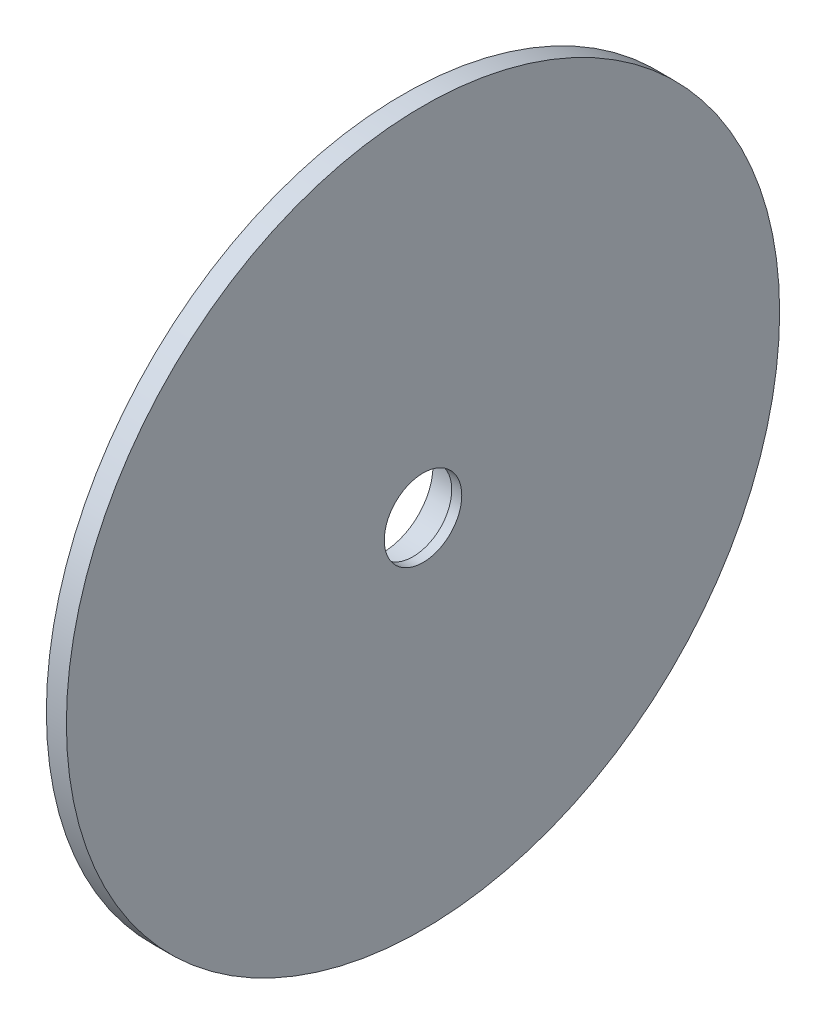
SolidWorks part; units mm, degrees
material "6061 Alloy"
ref_plane "Front Plane" through (0, 0, 0) normal (0, 0, 1) x (1, 0, 0)
ref_plane "Top Plane" through (0, 0, 0) normal (0, 1, 0) x (1, 0, 0)
ref_plane "Right Plane" through (0, 0, 0) normal (1, 0, 0) x (0, 0, -1)
sketch "Sketch1" plane through (0, 0, 0) normal (0, 0, 1) x (1, 0, 0)
  line L0 (0, 0) -> (-41.2566, 0) construction
  line L1 (-3.2523, 15.4808) -> (-7.2523, 15.4808)
  line L2 (-7.2523, 15.4808) -> (-7.2523, 20)
  line L3 (-7.2523, 20) -> (-26.2523, 20) construction
  line L4 (-26.2523, 20) -> (-26.2523, 100) construction
  line L5 (-26.2523, 100) -> (-32.2682, 100)
  line L6 (-32.2682, 100) -> (-32.2682, 105)
  line L7 (-32.2682, 105) -> (-3.2523, 105) construction
  line L8 (-3.2523, 105) -> (-3.2523, 15.4808)
  line L11 (-3.2523, 105) -> (-3.2523, 142.4808)
  line L12 (-3.2523, 142.4808) -> (-11.2523, 142.4808)
  line L13 (-11.2523, 142.4808) -> (-11.2523, 105)
  line L14 (-11.2523, 105) -> (-32.2682, 105)
  line L15 (-26.2523, 100) -> (-26.2523, 92.0483)
  line L16 (-26.2523, 92.0483) -> (-19.2523, 92.0483)
  line L17 (-19.2523, 92.0483) -> (-19.2523, 20)
  line L18 (-19.2523, 20) -> (-7.2523, 20)
  line L23 (-26.2523, -100) -> (-26.2523, 100) construction
  point P2 (-7.2523, 15.4808)
  point P12 (-26.2523, 90.0483)
  dimension "D1" = 20
  dimension "D2" = 12
  dimension "D4" = 5
  dimension "D5" = 127
  dimension "D6" = 100
  dimension "D7" = 4
  dimension "D8" = 2
revolve "Revolve1" add sketch "Sketch1" angle 360 about L0
